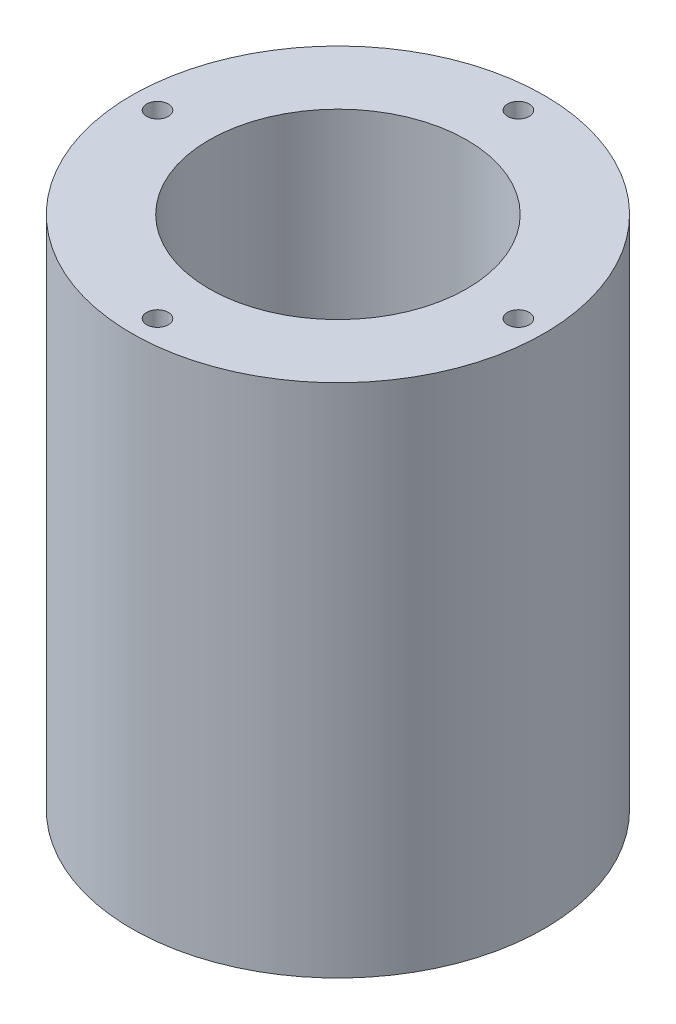
SolidWorks part; units mm, degrees
ref_plane "Front Plane" through (0, 0, 0) normal (0, 0, 1) x (1, 0, 0)
ref_plane "Top Plane" through (0, 0, 0) normal (0, 1, 0) x (1, 0, 0)
ref_plane "Right Plane" through (0, 0, 0) normal (1, 0, 0) x (0, 0, -1)
sketch "Sketch1" plane through (0, 0, 0) normal (0, 1, 0) x (1, 0, 0)
  circle A0 centre (0, 0) radius 40
  circle A1 centre (0, 0) radius 25
  dimension "D1" = 80
  dimension "D2" = 50
extrude "Boss-Extrude1" add sketch "Sketch1" along normal mid plane 100
sketch "Sketch2" plane through (0, 50, 0) normal (0, 1, 0) x (1, 0, 0)
  circle A0 centre (0, 35) radius 2.1
  circle A1 centre (35, 0) radius 2.1
  circle A2 centre (0, -35) radius 2.1
  circle A3 centre (-35, 0) radius 2.1
  point P12 (0, 0)
  dimension "D1" = 4.2
  dimension "D2" = 35
  dimension "D3" = 4
extrude "Cut-Extrude1" cut sketch "Sketch2" against normal blind 10
mirror "Mirror1" about plane through (0, 0, 0) normal (0, 1, 0) of "Cut-Extrude1"
sketch "Sketch3" plane through (0, -50, 0) normal (0, -1, 0) x (1, 0, 0)
  line L0 (0, 0) -> (0, 25) construction
  line L1 (0, 0) -> (4.3412, 24.6202)
  line L2 (0, 0) -> (-4.3412, 24.6202)
  line L3 (0, 0) -> (8.5505, 23.4923)
  line L4 (0, 0) -> (-8.5505, 23.4923)
  circle A0 centre (0, 0) radius 25 construction
  circle A1 centre (0, 0) radius 25
  circle A2 centre (0, 0) radius 15
  circle M13 centre (0, 0) radius 25
  dimension "D3" = 30
  dimension "D1" = 10
  dimension "D2" = 10
  dimension "D4" = 20
  dimension "D5" = 160
extrude "Boss-Extrude2" add sketch "Sketch3" against normal mid plane 24 from offset 50 contours A2 L0 L2 M13 | L0 A2 L1 A1 offset against normal yes
mirror "Mirror2" about plane through (0, 0, 0) normal (0, 0, 1) of "Boss-Extrude2"
sketch "Sketch4" plane through (0, 12, 0) normal (0, 1, 0) x (1, 0, 0)
  circle A0 centre (0, 0) radius 15
  circle A1 centre (0, 0) radius 11.1
  dimension "D1" = 30
  dimension "D2" = 22.2
extrude "Boss-Extrude3" add sketch "Sketch4" against normal blind 7
sketch "Sketch5" plane through (0, 5, 0) normal (0, -1, 0) x (1, 0, 0)
  circle A0 centre (0, 0) radius 9
  circle A1 centre (0, 0) radius 15
  dimension "D1" = 18
  dimension "D2" = 30
extrude "Boss-Extrude4" add sketch "Sketch5" along normal blind 10
sketch "Sketch6" plane through (0, -5, 0) normal (0, -1, 0) x (1, 0, 0)
  circle A0 centre (0, 0) radius 11.1
  circle A1 centre (0, 0) radius 15
  dimension "D1" = 22.2
  dimension "D2" = 30
extrude "Boss-Extrude5" add sketch "Sketch6" along normal up to surface (7 mm away) up to face at (0, -12, 19.8481)
fillet "Fillet1" radius 2 8 edges at (2.6047, 0, -14.7721) (-2.6047, 0, -14.7721) (2.6047, 0, 14.7721) (-2.6047, 0, 14.7721) (4.3412, 0, -24.6202) (-4.3412, 0, -24.6202) (-4.3412, 0, 24.6202) (4.3412, 0, 24.6202)
